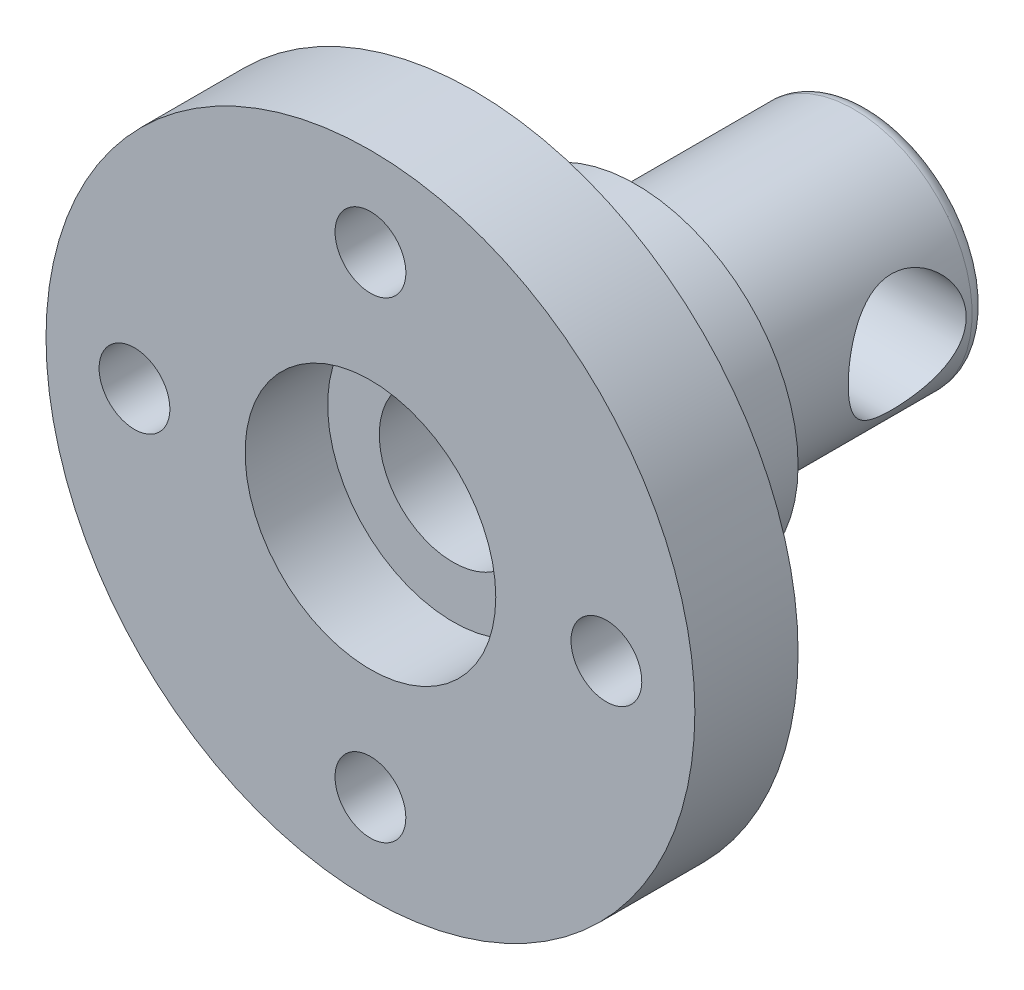
SolidWorks part; units mm, degrees
material "AISI 1020"
ref_plane "Front Plane" through (0, 0, 0) normal (0, 0, 1) x (1, 0, 0)
ref_plane "Top Plane" through (0, 0, 0) normal (0, 1, 0) x (1, 0, 0)
ref_plane "Right Plane" through (0, 0, 0) normal (1, 0, 0) x (0, 0, -1)
sketch "草图2" plane through (0, 0, 0) normal (0, 0, 1) x (1, 0, 0)
  circle A0 centre (0, 0) radius 11
  dimension "D1" = 22
extrude "凸台-拉伸1" add sketch "草图2" along normal blind 3.5
sketch "草图3" plane through (0, 0, 3.5) normal (0, 0, 1) x (1, 0, 0)
  circle A0 centre (0, 0) radius 4.25
  dimension "D1" = 8.5
extrude "切除-拉伸1" cut sketch "草图3" against normal blind 2.8
sketch "草图4" plane through (0, 0, 0) normal (0, 0, -1) x (-1, 0, 0)
  line L0 (0, 0) -> (0, 8)
  circle A0 centre (0, 8) radius 1.2
  dimension "D1" = 2.4
  dimension "D2" = 8
extrude "切除-拉伸2" cut sketch "草图4" against normal through all
pattern_circular "阵列(圆周)1" count 4 over 360 about axis through (0, 0, 0) along (0, 0, 1) of "切除-拉伸2"
sketch "草图6" plane through (0, 0, 0) normal (0, 0, -1) x (-1, 0, 0)
  circle A0 centre (0, 0) radius 4
  dimension "D1" = 8
extrude "凸台-拉伸2" add sketch "草图6" along normal blind 13.4
sketch "Sketch1" plane through (0, 0, 0) normal (1, 0, 0) x (0, 0, -1)
  circle A0 centre (10.7, 0) radius 2
  dimension "D1" = 10.7
  dimension "D2" = 4
extrude "Cut-Extrude1" cut sketch "Sketch1" against normal through all both and the other way through all
sketch "草图15" plane through (0, 0, 0) normal (0, 0, -1) x (-1, 0, 0)
  circle A0 centre (0, 0) radius 5.5
  dimension "D1" = 11
extrude "凸台-拉伸3" add sketch "草图15" along normal blind 5.5
fillet "圆角1" radius 0.5 1 edges at (-4, 0, -13.4)
sketch "草图11" plane through (0, 0, 0.7) normal (0, 0, 1) x (1, 0, 0)
  circle A0 centre (0, 0) radius 2.5
  dimension "D1" = 5
extrude "切除-拉伸6" cut sketch "草图11" against normal blind 2.2
